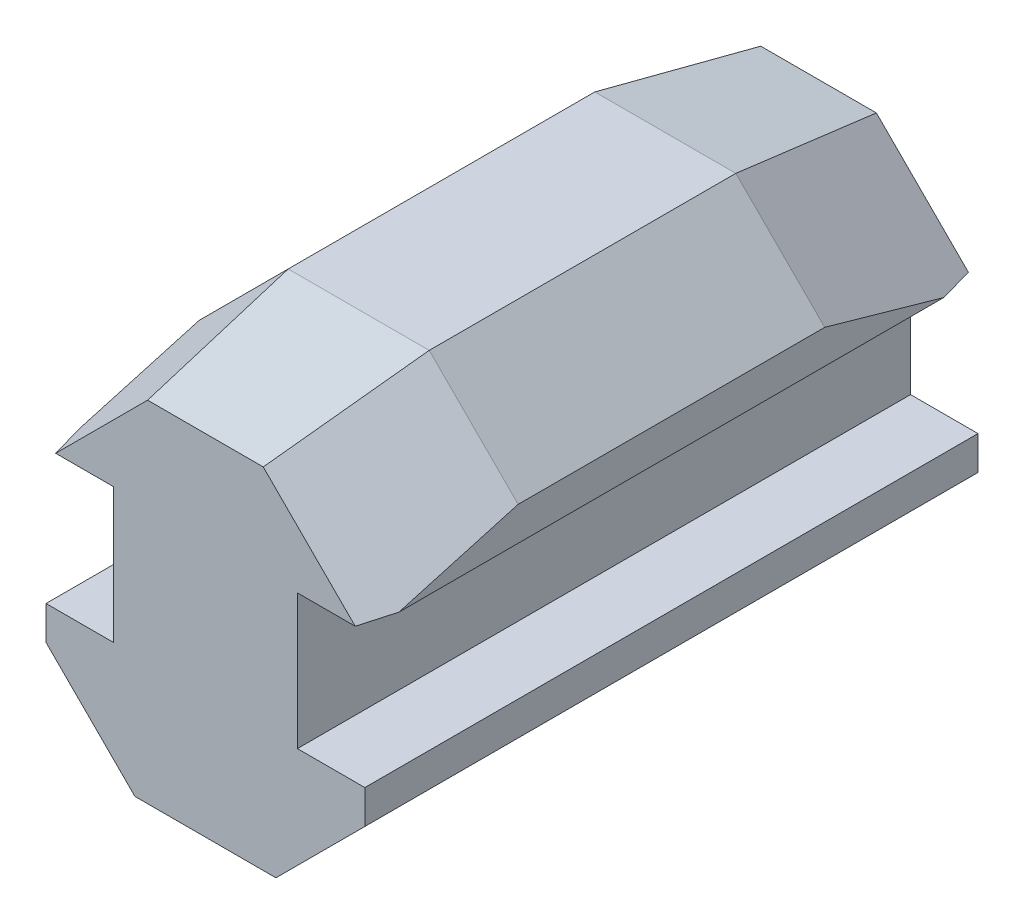
SolidWorks part; units mm, degrees
ref_plane "Front Plane" through (0, 0, 0) normal (0, 0, 1) x (1, 0, 0)
ref_plane "Top Plane" through (0, 0, 0) normal (0, 1, 0) x (1, 0, 0)
ref_plane "Right Plane" through (0, 0, 0) normal (1, 0, 0) x (0, 0, -1)
sketch "Sketch2" plane through (0, 0, 0) normal (0, 0, 1) x (1, 0, 0)
  line L0 (5.2, 3.3) -> (2.3, 6.2)
  line L1 (5.2, 2.2) -> (5.2, 3.3)
  line L3 (3, 2.2) -> (5.2, 2.2)
  line L5 (-3, 2.2) -> (-5.2, 2.2)
  line L6 (-5.2, 2.2) -> (-5.2, 3.3)
  line L7 (-5.2, 3.3) -> (-2.3, 6.2)
  line L8 (-2.3, 6.2) -> (2.3, 6.2)
  line L9 (0, -55) -> (0, 55) construction
  line L18 (55, 0) -> (-55, 0) construction
  line L19 (-2.3, -6.2) -> (2.3, -6.2)
  line L20 (-5.2, -3.3) -> (-2.3, -6.2)
  line L21 (-5.2, -2.2) -> (-5.2, -3.3)
  line L22 (-3, -2.2) -> (-5.2, -2.2)
  line L23 (3, -2.2) -> (5.2, -2.2)
  line L24 (5.2, -2.2) -> (5.2, -3.3)
  line L25 (5.2, -3.3) -> (2.3, -6.2)
  line L26 (-3, 2.2) -> (-3, -2.2)
  line L28 (3, 2.2) -> (3, -2.2)
  point P2 (0, 6.2)
  point P12 (0, 0)
  point P23 (0, -6.2)
  dimension "D1" = 270
  dimension "D2" = 1.1
  dimension "D4" = 5.2
  dimension "D6" = 4
extrude "Boss-Extrude2" add sketch "Sketch2" along normal mid plane 20
chamfer "Chamfer1" distance 5 distance2 1 3 edges at (-3.75, 4.75, 10) (3.75, 4.75, 10) (0, 6.2, 10)
chamfer "Chamfer2" distance 1 distance2 5 3 edges at (-3.75, 4.75, -10) (0, 6.2, -10) (3.75, 4.75, -10)
